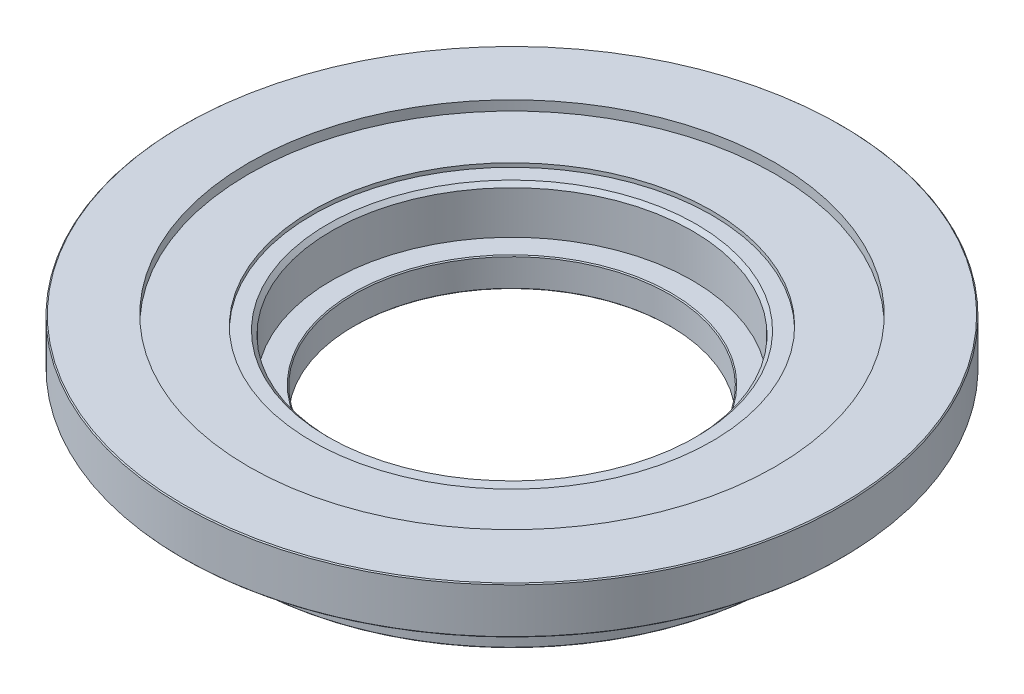
SolidWorks part; units mm, degrees
ref_plane "前基準面" through (0, 0, 0) normal (0, 0, 1) x (1, 0, 0)
ref_plane "上基準面" through (0, 0, 0) normal (0, 1, 0) x (1, 0, 0)
ref_plane "右基準面" through (0, 0, 0) normal (1, 0, 0) x (0, 0, -1)
sketch "草圖1" plane through (0, 0, 0) normal (0, 0, 1) x (1, 0, 0)
  line L0 (169, 56) -> (0, 56)
  line L1 (0, 56) -> (0, 32)
  line L2 (0, 32) -> (169, 32)
  line L3 (169, 32) -> (169, 56)
  line L4 (0, 56) -> (0, 32) construction
revolve "旋轉1" add sketch "草圖1" angle 360 about L4
sketch "草圖2" plane through (0, 32, 0) normal (0, -1, 0) x (1, 0, 0)
  circle A0 centre (0, 0) radius 137.5
extrude "填料-伸長1" add sketch "草圖2" along normal blind 27
sketch "草圖3" plane through (0, 0, 0) normal (0, 0, 1) x (1, 0, 0)
  line L0 (135, 56) -> (0, 56)
  line L1 (0, 56) -> (0, 5)
  line L2 (0, 5) -> (132.5, 5)
  line L3 (132.5, 5) -> (132.5, 10)
  line L4 (132.5, 10) -> (81, 10)
  line L5 (81, 10) -> (81, 25)
  line L6 (81, 25) -> (92.5, 25)
  line L7 (92.5, 25) -> (92.5, 49)
  line L8 (92.5, 49) -> (102.5, 49)
  line L9 (102.5, 49) -> (102.5, 51)
  line L10 (102.5, 51) -> (135, 51)
  line L11 (135, 51) -> (135, 56)
  line L12 (0, 56) -> (0, 5) construction
revolve "除料-旋轉1" cut sketch "草圖3" angle 360 about L12
chamfer "導角1" distance 0.5 angle 45 6 edges at (0, 56, -169) (0, 5, -132.5) (0, 25, -81) (0, 32, -169) (0, 10, -81) (0, 5, -137.5)
chamfer "導角2" distance 2 angle 45 1 edges at (0, 49, -92.5)
